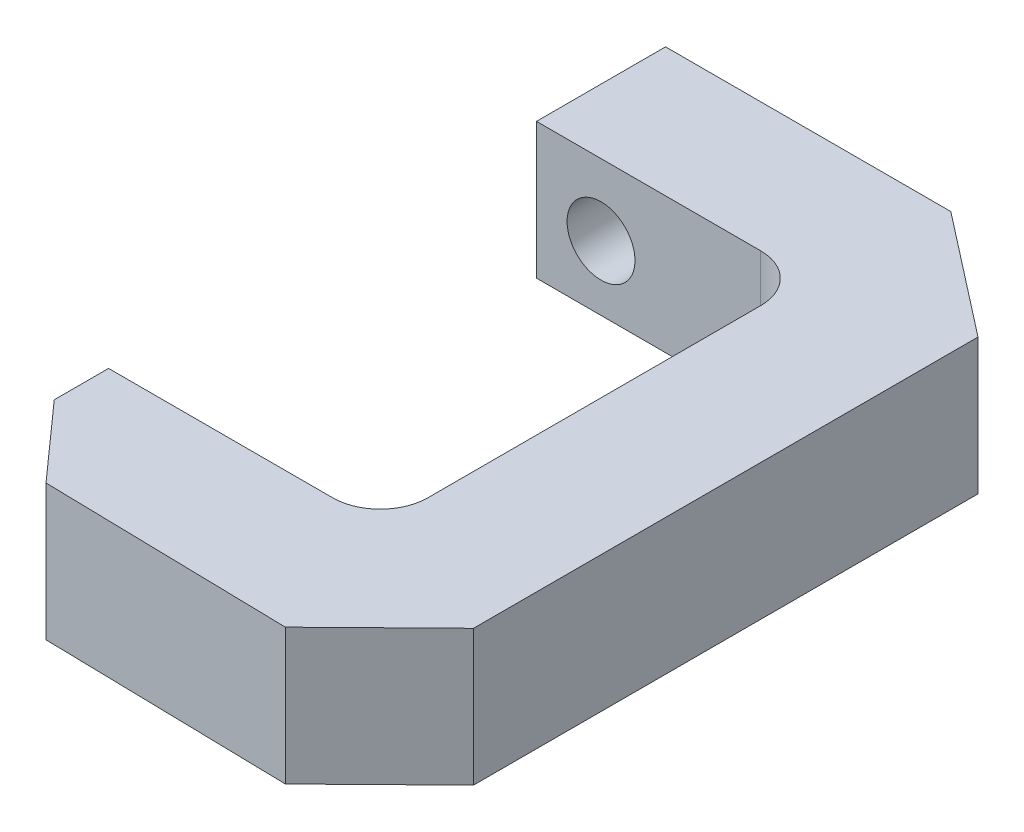
SolidWorks part; units mm, degrees
ref_plane "Front Plane" through (0, 0, 0) normal (0, 0, 1) x (1, 0, 0)
ref_plane "Top Plane" through (0, 0, 0) normal (0, 1, 0) x (1, 0, 0)
ref_plane "Right Plane" through (0, 0, 0) normal (1, 0, 0) x (0, 0, -1)
sketch "Sketch1" plane through (0, 0, 0) normal (0, 1, 0) x (1, 0, 0)
  line L0 (0, 0) -> (0, 101)
  line L1 (0, 101) -> (60, 101)
  line L2 (60, 101) -> (60, -1.276)
  line L3 (60, -1.276) -> (0, 0)
  dimension "D1" = 101
  dimension "D2" = 60
extrude "Boss-Extrude1" add sketch "Sketch1" along normal blind 20
sketch "Sketch2" plane through (0, 20, 0) normal (0, 1, 0) x (1, 0, 0)
  line L0 (60, 101) -> (42, 101)
  line L1 (60, 101) -> (0, 101) construction
  line L2 (42, 101) -> (60, 87)
  line L3 (60, -1.276) -> (60, 101) construction
  line L4 (60, 87) -> (60, 101)
  dimension "D1" = 14
  dimension "D2" = 18
extrude "Cut-Extrude1" cut sketch "Sketch2" against normal blind 20
sketch "Sketch3" plane through (0, 20, 0) normal (0, 1, 0) x (1, 0, 0)
  line L0 (60, -1.276) -> (46, -0.9783)
  line L1 (46, -0.9783) -> (60, 12.724)
  line L2 (60, -1.276) -> (60, 87) construction
  line L3 (60, 12.724) -> (60, -1.276)
  line L4 (0, 0) -> (60, -1.276) construction
  line L5 (10, -0.2127) -> (0, 0)
  line L6 (0, 0) -> (0, 11)
  line L7 (0, 101) -> (0, 0) construction
  line L8 (0, 11) -> (10, -0.2127)
  dimension "D1" = 14
  dimension "D2" = 14
  dimension "D3" = 11
  dimension "D4" = 10
extrude "Cut-Extrude2" cut sketch "Sketch3" against normal blind 20
sketch "Sketch4" plane through (0, 20, 0) normal (0, 1, 0) x (1, 0, 0)
  line L1 (0, 101) -> (0, 11) construction
  line L3 (0, 82) -> (36.5, 82)
  line L4 (36.5, 82) -> (36.5, 19)
  line L5 (36.5, 19) -> (0, 19)
  line L6 (0, 82) -> (0, 19)
  dimension "D3" = 36.5
extrude "Cut-Extrude3" cut sketch "Sketch4" against normal blind 20
fillet "Fillet1" radius 7 1 edges at (36.5, 10, -82)
fillet "Fillet2" radius 7 1 edges at (36.5, 10, -19)
sketch "Sketch5" plane through (0, 0, -101) normal (0, 0, -1) x (-1, 0, 0)
  circle A0 centre (-9.5, 9.5) radius 5
extrude "Cut-Extrude4" cut sketch "Sketch5" against normal blind 20
sketch "Sketch7" plane through (0, 20, 0) normal (0, 1, 0) x (1, 0, 0)
  line L0 (29.5, 82) -> (40, 82)
  line L1 (40, 82) -> (40, 19)
  line L2 (40, 19) -> (0, 19)
  line L3 (0, 19) -> (0, 82)
  line L4 (0, 82) -> (29.5, 82)
  point P3 (0, 19)
extrude "Cut-Extrude5" cut sketch "Sketch7" against normal blind 20
fillet "Fillet3" radius 7 1 edges at (40, 10, -82)
fillet "Fillet4" radius 7 1 edges at (40, 10, -19)
